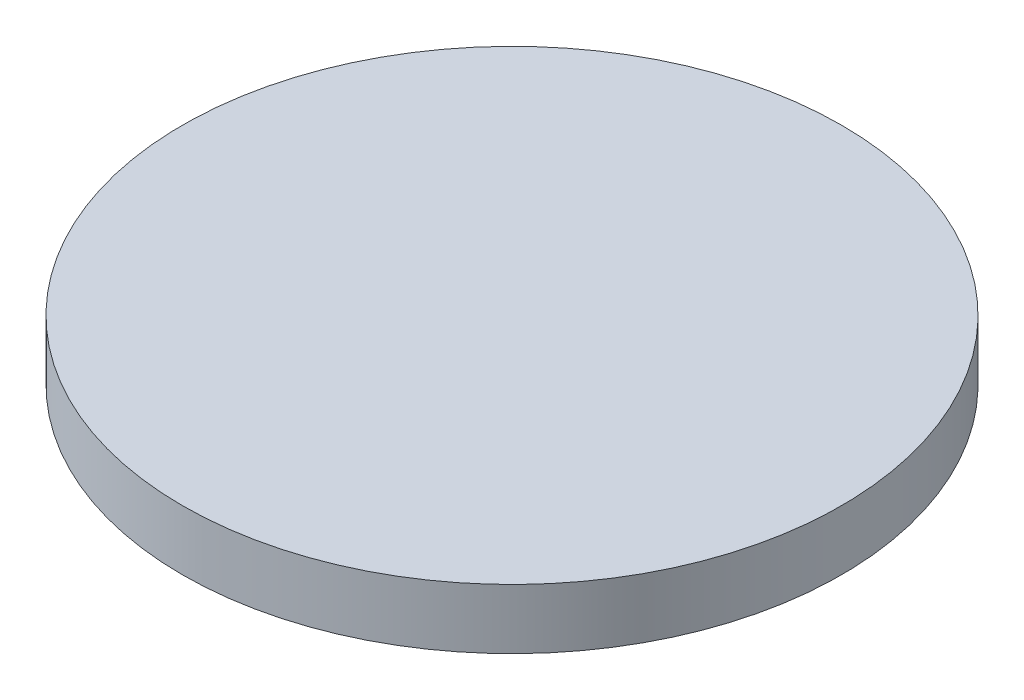
SolidWorks part; units mm, degrees
material "Natural Rubber"
ref_plane "Front Plane" through (0, 0, 0) normal (0, 0, 1) x (1, 0, 0)
ref_plane "Top Plane" through (0, 0, 0) normal (0, 1, 0) x (1, 0, 0)
ref_plane "Right Plane" through (0, 0, 0) normal (1, 0, 0) x (0, 0, -1)
sketch "BaseS" plane through (0, 0, 0) normal (0, 1, 0) x (1, 0, 0)
  circle A0 centre (0, 0) radius 2.75
  dimension "D1" = 5.5
extrude "BASE" add sketch "BaseS" against normal blind 0.5
